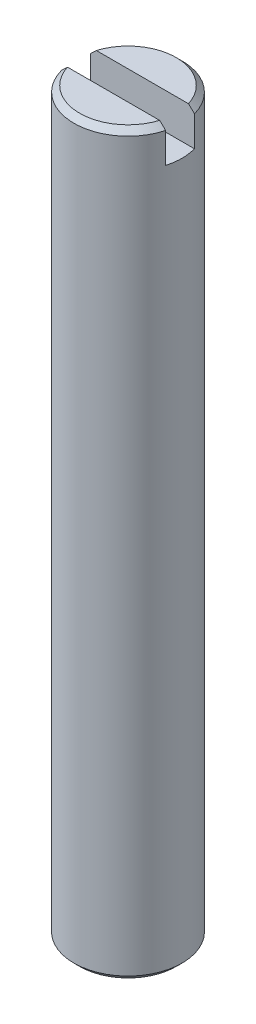
SolidWorks part; units mm, degrees
ref_plane "Front Plane" through (0, 0, 0) normal (0, 0, 1) x (1, 0, 0)
ref_plane "Top Plane" through (0, 0, 0) normal (0, 1, 0) x (1, 0, 0)
ref_plane "Right Plane" through (0, 0, 0) normal (1, 0, 0) x (0, 0, -1)
sketch "Sketch1" plane through (0, 0, 0) normal (0, 1, 0) x (1, 0, 0)
  circle A0 centre (0, 0) radius 187.5
extrude "Boss-Extrude1" add sketch "Sketch1" along normal blind 2563 contours A0
sketch "Sketch2" plane through (0, 2563, 0) normal (0, 1, 0) x (1, 0, 0)
  line L1 (187.5, 50) -> (-187.5, 50)
  line L2 (187.5, 50) -> (187.5, -50)
  line L3 (187.5, -50) -> (-187.5, -50)
  line L4 (-187.5, 50) -> (-187.5, -50)
  line L5 (187.5, 50) -> (-187.5, -50) construction
  line L6 (187.5, -50) -> (-187.5, 50) construction
  point P0 (0, 0)
extrude "Cut-Extrude1" cut sketch "Sketch2" against normal blind 125
chamfer "Chamfer1" distance 20 angle 45 2 edges at (0, 2563, -187.5) (0, 2563, 187.5)
chamfer "Chamfer2" distance 20 angle 45 1 edges at (0, 0, 187.5)
